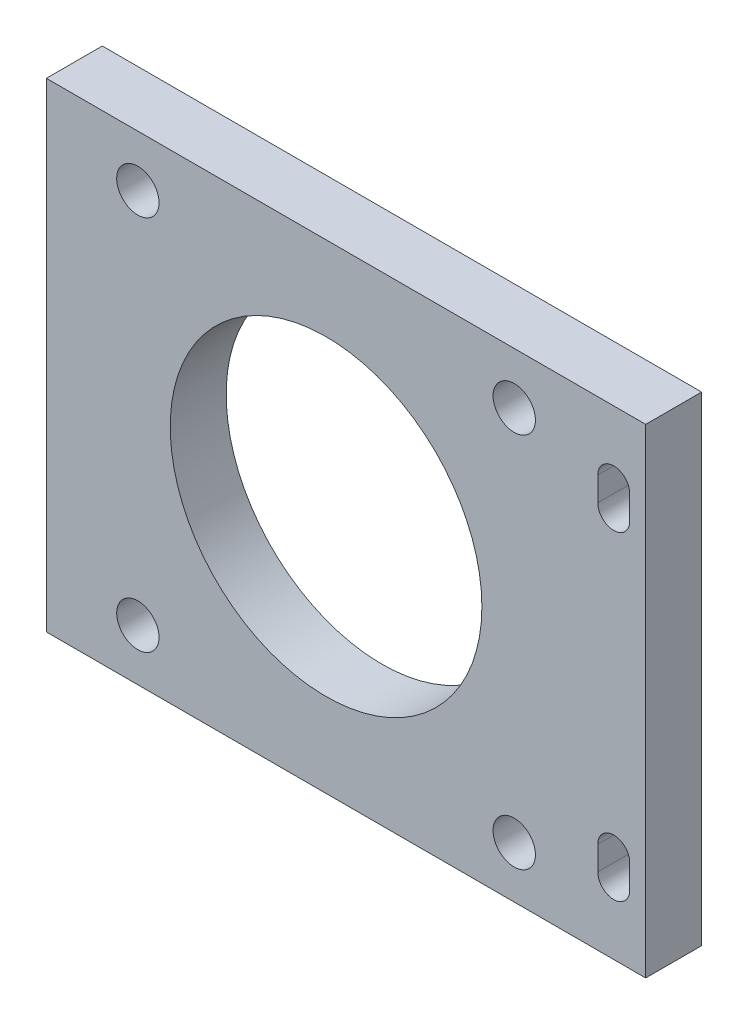
SolidWorks part; units mm, degrees
ref_plane "Front Plane" through (0, 0, 0) normal (0, 0, 1) x (1, 0, 0)
ref_plane "Top Plane" through (0, 0, 0) normal (0, 1, 0) x (1, 0, 0)
ref_plane "Right Plane" through (0, 0, 0) normal (1, 0, 0) x (0, 0, -1)
sketch "Sketch1" plane through (0, 0, 0) normal (0, 0, 1) x (1, 0, 0)
  line L1 (37.5, -30) -> (-37.5, -30)
  line L2 (37.5, -30) -> (37.5, 30)
  line L3 (37.5, 30) -> (-37.5, 30)
  line L4 (-37.5, -30) -> (-37.5, 30)
  line L5 (37.5, -30) -> (-37.5, 30) construction
  line L6 (37.5, 30) -> (-37.5, -30) construction
  point P0 (0, 0)
  dimension "D1" = 60
  dimension "D2" = 75
extrude "Boss-Extrude1" add sketch "Sketch1" along normal blind 7
sketch "Sketch2" plane through (0, 0, 0) normal (0, 0, -1) x (-1, 0, 0)
  line L0 (-37.5, 0) -> (37.5, 0) construction
  line L1 (-37.5, -30) -> (-37.5, 30) construction
  line L2 (37.5, 30) -> (37.5, -30) construction
  circle A0 centre (2.5, 0) radius 33.3047 construction
  point P7 (2.5, 0)
  point P19 (-21.05, -23.55)
  point P20 (26.05, -23.55)
  point P21 (26.05, 23.55)
  point P22 (-21.05, 23.55)
  dimension "D1" = 47.1
  dimension "D2" = 35
  dimension "D3" = 47.1
hole_wizard "Ø5.3 (5.3) Diameter Hole1" positions "3DSketch1" profile "Sketch3" hole size "Ø5.3" standard "ISO" end condition through all
sketch3d "3DSketch1"
  point P17 (21.05, 23.55, 0)
  point P20 (-26.05, 23.55, 0)
  point P23 (-26.05, -23.55, 0)
  point P30 (21.05, -23.55, 0)
sketch "Sketch3" plane through (21.05, 23.55, 0) normal (1, 0, 0) x (0, 1, 0)
  line L0 (0, 0) -> (0, 7)
  line L1 (0, 7) -> (2.65, 7)
  line L2 (2.65, 7) -> (2.65, 0)
  line L5 (2.65, 0) -> (0, 0)
  line L11 (0, -6.35) -> (0, 107.95) construction
  dimension "Thru Hole Dia." = 5.3
  dimension "Thru Hole Depth" = 7
hole_wizard "Ø10.0 (10) Diameter Hole1" positions "3DSketch2" profile "Sketch4" hole size "Ø10.0" standard "ISO" end condition through all
sketch3d "3DSketch2"
  point P0 (-2.5, 0, 0)
sketch "Sketch4" plane through (-2.5, 0, 0) normal (1, 0, 0) x (0, 1, 0)
  line L0 (0, 0) -> (0, 7)
  line L1 (0, 7) -> (5, 7)
  line L2 (5, 7) -> (5, 0)
  line L5 (5, 0) -> (0, 0)
  line L11 (0, -6.35) -> (0, 107.95) construction
  dimension "Thru Hole Dia." = 10
  dimension "Thru Hole Depth" = 7
sketch "Sketch5" plane through (0, 0, 7) normal (0, 0, 1) x (1, 0, 0)
  circle A0 centre (-2.5, 0) radius 19.5
  dimension "D1" = 39
extrude "Cut-Extrude1" cut sketch "Sketch5" against normal through all
sketch "Sketch6" plane through (0, 0, 0) normal (0, 0, -1) x (-1, 0, 0)
  line L0 (-33.5, 30) -> (-33.5, -30) construction
  line L1 (-37.5, 30) -> (37.5, 30) construction
  line L2 (37.5, -30) -> (-37.5, -30) construction
  line L3 (-37.5, -30) -> (-37.5, 30) construction
  line L4 (-33.5, 18.5) -> (-33.5, 21.5) construction
  line L5 (-35.5, 18.5) -> (-35.5, 21.5)
  line L6 (-31.5, 18.5) -> (-31.5, 21.5)
  line L7 (-37.5, 0) -> (37.5, 0) construction
  line L8 (37.5, 30) -> (37.5, -30) construction
  line L9 (-33.5, -18.5) -> (-33.5, -21.5) construction
  line L10 (-35.5, -18.5) -> (-35.5, -21.5)
  line L11 (-31.5, -18.5) -> (-31.5, -21.5)
  arc A0 (-35.5, 18.5) -> (-31.5, 18.5) centre (-33.5, 18.5) ccw
  arc A1 (-31.5, 21.5) -> (-35.5, 21.5) centre (-33.5, 21.5) ccw
  arc A2 (-35.5, -18.5) -> (-31.5, -18.5) centre (-33.5, -18.5) cw
  arc A3 (-31.5, -21.5) -> (-35.5, -21.5) centre (-33.5, -21.5) cw
  point P10 (-33.5, 20)
  point P24 (-33.5, -20)
  dimension "D1" = 4
  dimension "D2" = 4
  dimension "D3" = 3
  dimension "D4" = 10
extrude "Cut-Extrude2" cut sketch "Sketch6" against normal through all
